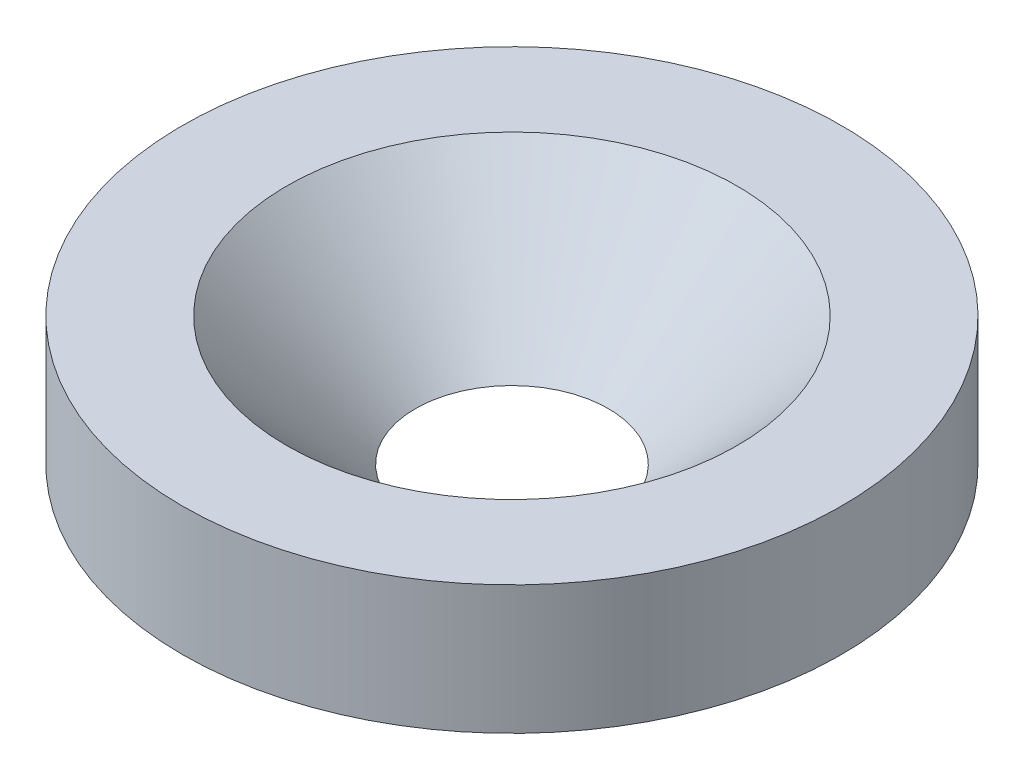
SolidWorks part; units mm, degrees
ref_plane "Front Plane" through (0, 0, 0) normal (0, 0, 1) x (1, 0, 0)
ref_plane "Top Plane" through (0, 0, 0) normal (0, 1, 0) x (1, 0, 0)
ref_plane "Right Plane" through (0, 0, 0) normal (1, 0, 0) x (0, 0, -1)
sketch "Sketch1" plane through (0, 0, 0) normal (0, 0, 1) x (1, 0, 0)
  line L0 (0, 18.341) -> (0, 0) construction
  line L1 (14, 8) -> (20.5, 8)
  line L2 (20.5, 8) -> (20.5, 0)
  line L3 (20.5, 0) -> (6, 0)
  line L4 (6, 0) -> (14, 8)
  dimension "D1" = 45
  dimension "D2" = 6
  dimension "D3" = 8
  dimension "D4" = 20.5
revolve "Revolve1" add sketch "Sketch1" angle 360 about L0
